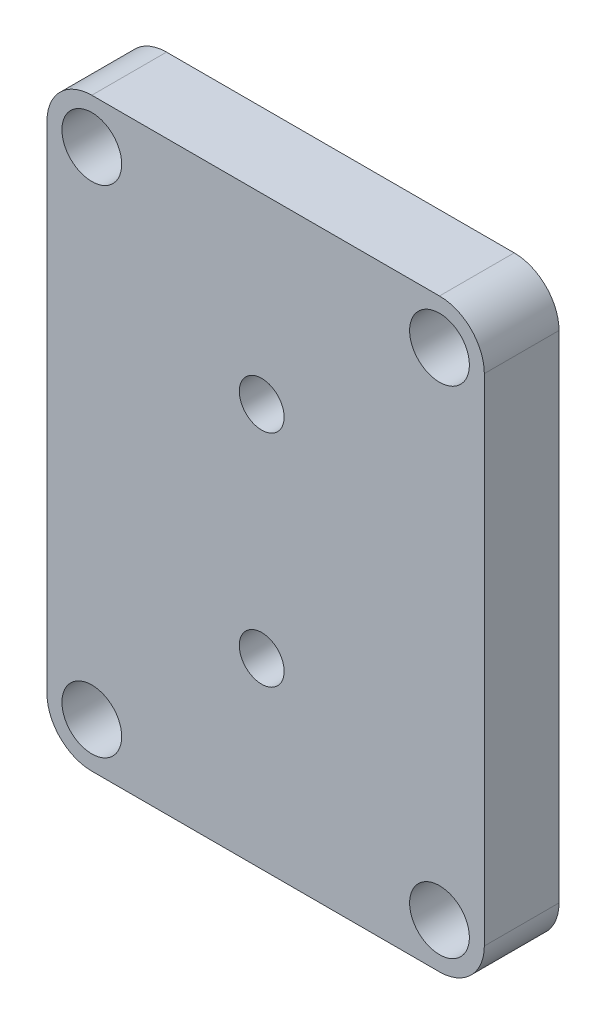
SolidWorks part; units mm, degrees
ref_plane "Front Plane" through (0, 0, 0) normal (0, 0, 1) x (1, 0, 0)
ref_plane "Top Plane" through (0, 0, 0) normal (0, 1, 0) x (1, 0, 0)
ref_plane "Right Plane" through (0, 0, 0) normal (1, 0, 0) x (0, 0, -1)
sketch "Esquisse1" plane through (0, 0, 0) normal (0, 0, 1) x (1, 0, 0)
  line L0 (0, -22.0343) -> (29.2719, -22.0343) construction
  line L1 (3, -2.4446) -> (26.2719, -2.4446)
  line L2 (0, -5.4446) -> (0, -38.624)
  line L3 (3, -41.624) -> (26.2719, -41.624)
  line L4 (29.2719, -5.4446) -> (29.2719, -38.624)
  line L5 (14.3726, -14.6693) -> (14.3726, -29.3993) construction
  arc A0 (3, -41.624) -> (0, -38.624) centre (3, -38.624) cw
  arc A1 (29.2719, -38.624) -> (26.2719, -41.624) centre (26.2719, -38.624) cw
  arc A2 (29.2719, -5.4446) -> (26.2719, -2.4446) centre (26.2719, -5.4446) ccw
  arc A3 (0, -5.4446) -> (3, -2.4446) centre (3, -5.4446) cw
  circle A4 centre (14.3726, -14.6693) radius 1.5
  circle A5 centre (14.3726, -29.3993) radius 1.5
  circle A6 centre (3, -5.4446) radius 2
  circle A7 centre (26.2719, -5.4446) radius 2
  circle A8 centre (3, -38.624) radius 2
  circle A9 centre (26.2719, -38.624) radius 2
  point P18 (14.3726, -22.0343)
  dimension "D1" = 3
  dimension "D2" = 3
  dimension "D3" = 3
  dimension "D5" = 4
  dimension "D4" = 14.73
extrude "Boss.-Extru.1" add sketch "Esquisse1" along normal blind 5
